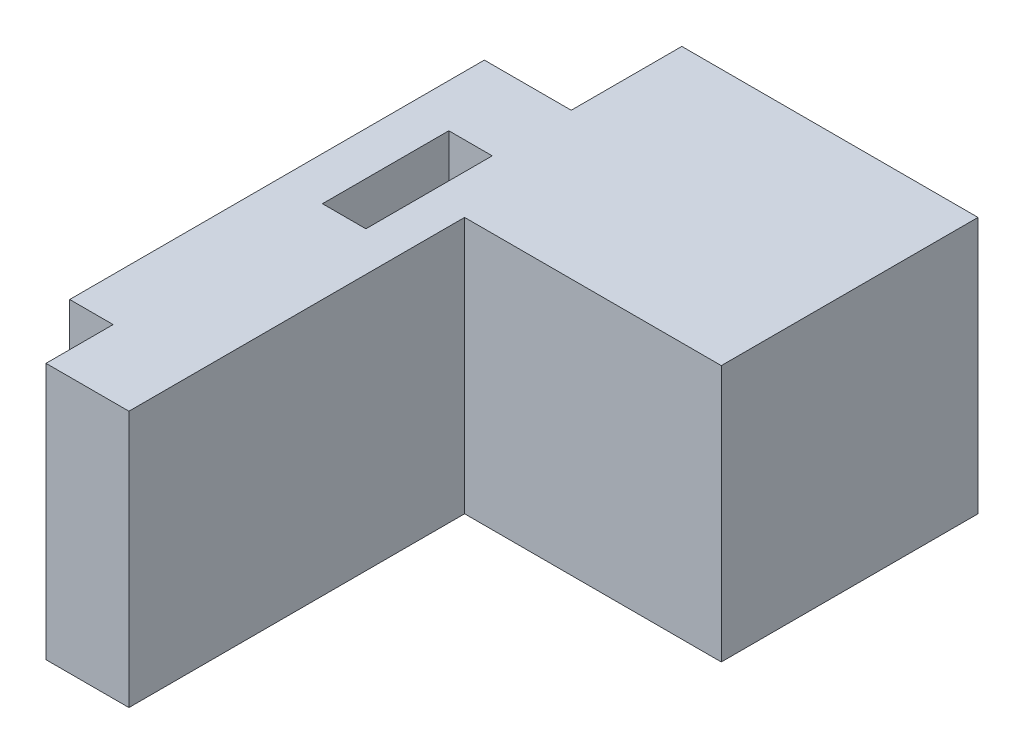
SolidWorks part; units mm, degrees
ref_plane "Ebene vorne" through (0, 0, 0) normal (0, 0, 1) x (1, 0, 0)
ref_plane "Ebene oben" through (0, 0, 0) normal (0, 1, 0) x (1, 0, 0)
ref_plane "Ebene rechts" through (0, 0, 0) normal (1, 0, 0) x (0, 0, -1)
sketch "Skizze1" plane through (0, 0, 0) normal (0, 1, 0) x (1, 0, 0)
  line L1 (-37.5, -32.5) -> (37.5, -32.5)
  line L2 (-37.5, -32.5) -> (-37.5, 32.5)
  line L3 (-37.5, 32.5) -> (37.5, 32.5)
  line L4 (37.5, -32.5) -> (37.5, 32.5)
  line L5 (-37.5, -32.5) -> (37.5, 32.5) construction
  line L6 (-37.5, 32.5) -> (37.5, -32.5) construction
  line L7 (-37.5, -32.5) -> (-27.5, -32.5)
  line L8 (-37.5, -32.5) -> (-37.5, -117.5)
  line L9 (-37.5, -117.5) -> (-27.5, -117.5)
  line L10 (-27.5, -32.5) -> (-27.5, -117.5)
  line L11 (-37.5, -32.5) -> (-27.5, -117.5) construction
  line L12 (-37.5, -117.5) -> (-27.5, -32.5) construction
  line L14 (-37.5, -117.5) -> (-37.5, -66.2841)
  line L17 (-37.5, -117.5) -> (-48.5, -117.5)
  line L18 (-37.5, -117.5) -> (-37.5, -47.5)
  line L19 (-37.5, -47.5) -> (-48.5, -47.5)
  line L24 (-48.5, -117.5) -> (-48.5, -47.5)
  line L25 (-37.5, -117.5) -> (-48.5, -47.5) construction
  line L26 (-37.5, -47.5) -> (-48.5, -117.5) construction
  line L31 (-48.5, -100.5) -> (-59.5, -100.5)
  line L32 (-48.5, -100.5) -> (-48.5, 4.5)
  line L33 (-48.5, 4.5) -> (-59.5, 4.5)
  line L34 (-59.5, -100.5) -> (-59.5, 4.5)
  line L35 (-48.5, -100.5) -> (-59.5, 4.5) construction
  line L36 (-48.5, 4.5) -> (-59.5, -100.5) construction
  line L37 (-48.5, 4.5) -> (-37.5, 4.5)
  line L38 (-48.5, 4.5) -> (-48.5, -15.5)
  line L39 (-48.5, -15.5) -> (-37.5, -15.5)
  line L40 (-37.5, 4.5) -> (-37.5, -15.5)
  line L41 (-48.5, 4.5) -> (-37.5, -15.5) construction
  line L42 (-48.5, -15.5) -> (-37.5, 4.5) construction
  point P0 (0, 0)
  point P9 (-32.5, -75)
  point P14 (-43, -82.5)
  point P19 (-54, -48)
  point P23 (-43, -5.5)
  dimension "D1" = 75
  dimension "D2" = 65
  dimension "D3" = 10
  dimension "D4" = 85
  dimension "D5" = 11
  dimension "D6" = 70
  dimension "D7" = 18
  dimension "D8" = 11
  dimension "D9" = 105
  dimension "D10" = 20
extrude "Aufsatz-Linear austragen1" add sketch "Skizze1" along normal blind 65 contours L1 L4 L3 L2 | L32 L39 L2 L37 | L34 L31 L24 L32 L33 | L24 L17 L8 L19 | L10 L1 L8 L9
